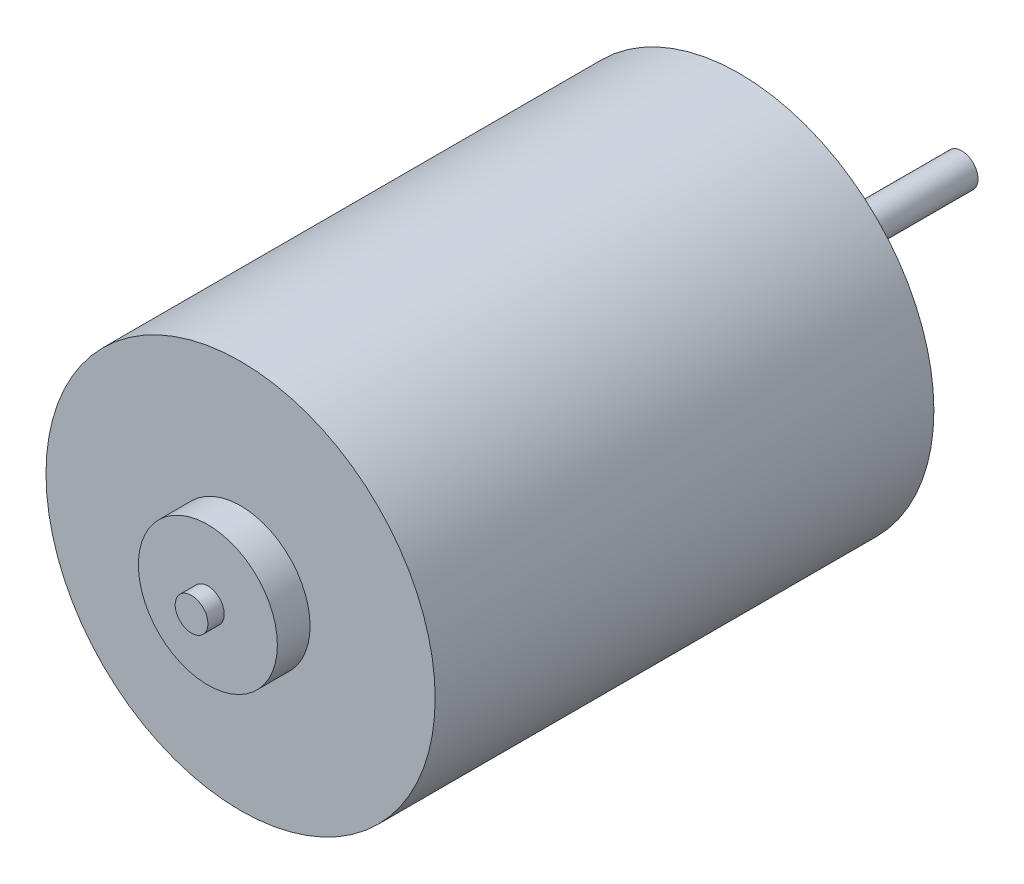
SolidWorks part; units mm, degrees
ref_plane "Front Plane" through (0, 0, 0) normal (0, 0, 1) x (1, 0, 0)
ref_plane "Top Plane" through (0, 0, 0) normal (0, 1, 0) x (1, 0, 0)
ref_plane "Right Plane" through (0, 0, 0) normal (1, 0, 0) x (0, 0, -1)
sketch "Sketch2" plane through (0, 0, 0) normal (0, 0, 1) x (1, 0, 0)
  circle A0 centre (0, 0) radius 11.9
  dimension "D1" = 23.8
extrude "Boss-Extrude1" add sketch "Sketch2" along normal blind 30.5
sketch "Sketch3" plane through (0, 0, 30.5) normal (0, 0, 1) x (1, 0, 0)
  circle A0 centre (0, 0) radius 4.25
  dimension "D1" = 8.5
extrude "Boss-Extrude2" add sketch "Sketch3" along normal blind 2
sketch "Sketch4" plane through (0, 0, 0) normal (0, 0, -1) x (-1, 0, 0)
  circle A0 centre (0, 0) radius 3.15
  dimension "D1" = 6.3
extrude "Boss-Extrude3" add sketch "Sketch4" along normal blind 1.6
sketch "Sketch5" plane through (0, 0, -1.6) normal (0, 0, -1) x (-1, 0, 0)
  circle A0 centre (0, 0) radius 1
  dimension "D1" = 2
extrude "Boss-Extrude4" add sketch "Sketch5" along normal blind 12
sketch "Sketch6" plane through (0, 0, 32.5) normal (0, 0, 1) x (1, 0, 0)
  circle A0 centre (0, 0) radius 1
  dimension "D1" = 2
extrude "Boss-Extrude5" add sketch "Sketch6" along normal blind 1
